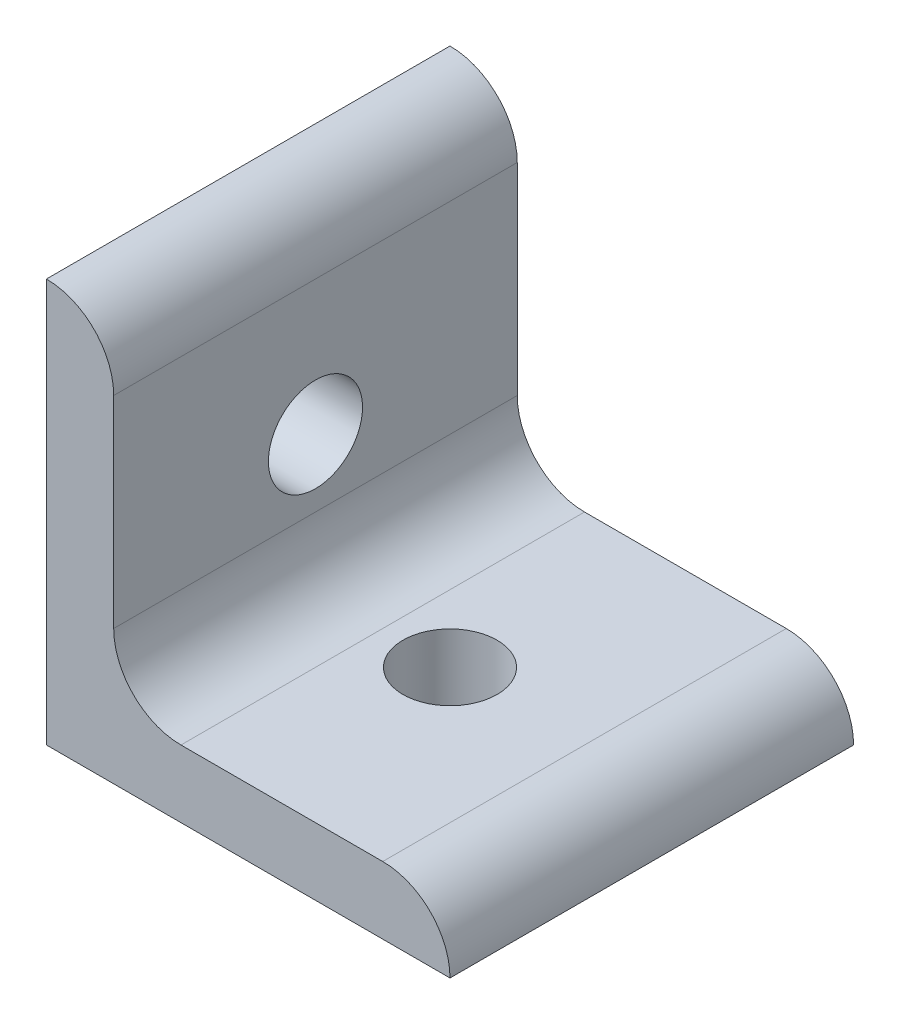
SolidWorks part; units mm, degrees
ref_plane "Front Plane" through (0, 0, 0) normal (0, 0, 1) x (1, 0, 0)
ref_plane "Top Plane" through (0, 0, 0) normal (0, 1, 0) x (1, 0, 0)
ref_plane "Right Plane" through (0, 0, 0) normal (1, 0, 0) x (0, 0, -1)
sketch "Sketch1" plane through (0, 0, 0) normal (0, 0, 1) x (1, 0, 0)
  line L0 (0, 0) -> (0, 30)
  line L1 (5, 25) -> (5, 30) construction
  line L2 (5, 25) -> (5, 10)
  line L3 (10, 5) -> (25, 5)
  line L4 (5, 30) -> (0, 30) construction
  line L5 (30, 0) -> (0, 0)
  line L6 (25, 5) -> (30, 5) construction
  line L7 (30, 5) -> (30, 0) construction
  arc A0 (5, 25) -> (0, 30) centre (0, 25) ccw
  arc A1 (30, 0) -> (25, 5) centre (25, 0) ccw
  arc A2 (5, 10) -> (10, 5) centre (10, 10) ccw
  point P10 (5, 27.5)
  dimension "E" = 5
  dimension "D" = 5
  dimension "C" = 30
  dimension "B" = 30
extrude "Boss-Extrude1" add sketch "Sketch1" along normal mid plane 30
sketch "Sketch2" plane through (0, 0, 0) normal (0, 1, 0) x (1, 0, 0)
  line L0 (0, 0) -> (15, 0) construction
  circle A0 centre (15, 0) radius 3.5
extrude "Cut-Extrude1" cut sketch "Sketch2" along normal through all
sketch "Sketch3" plane through (0, 0, 0) normal (1, 0, 0) x (0, 0, -1)
  line L0 (0, 0) -> (0, 15) construction
  circle A0 centre (0, 15) radius 3.5
  dimension "D1" = 15
extrude "Cut-Extrude2" cut sketch "Sketch3" along normal through all
equation "\"E@Sketch3\" = \"E@Sketch2\""
equation "\"D1@Sketch3\" = \"D1@Sketch2\""
